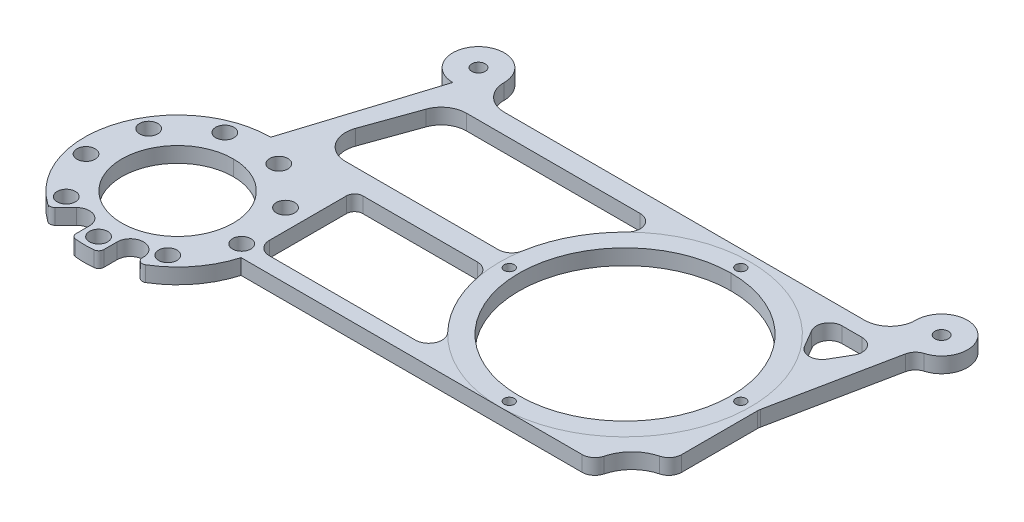
SolidWorks part; units mm, degrees
material "6061-T6 (SS)"
ref_plane "Front Plane" through (0, 0, 0) normal (0, 0, 1) x (1, 0, 0)
ref_plane "Top Plane" through (0, 0, 0) normal (0, 1, 0) x (1, 0, 0)
ref_plane "Right Plane" through (0, 0, 0) normal (1, 0, 0) x (0, 0, -1)
sketch "Sketch5" plane through (0, 0, 0) normal (0, 1, 0) x (-1, 0, 0)
  line L0 (0, 0) -> (0, 61.9125) construction
  line L1 (0, 0) -> (0, -61.9125) construction
  line L2 (0, 0) -> (-61.9125, 0) construction
  line L3 (0, 0) -> (61.9125, 0) construction
  line L4 (171.7713, 49.0982) -> (171.7713, 88.098) construction
  line L5 (-91.0543, 67.1325) -> (-91.0543, -77.9015)
  line L6 (18.2889, -77.9015) -> (18.2889, -74.5116)
  line L7 (18.2889, -77.9015) -> (150.2457, -77.9015)
  line L8 (-78.3543, -77.9015) -> (18.2889, -77.9015)
  line L9 (-78.3543, 67.1325) -> (-78.3543, -77.9015)
  line L14 (-65.6543, 67.1325) -> (0, 61.9125)
  line L15 (0, 61.9125) -> (148.0838, 88.5001)
  line L16 (150.2457, -65.2015) -> (171.7713, 3.1242)
  line L17 (0, 61.9125) -> (148.0838, 88.5001)
  line L18 (-52.9543, -65.2015) -> (124.8457, -65.2015)
  line L19 (167.2211, 94.8465) -> (167.2211, 96.424) construction
  line L22 (194.9712, 86.4149) -> (189.7063, 81.15)
  line L23 (178.6101, 85.7462) -> (178.6101, 92.3189)
  line L24 (164.9325, 92.3189) -> (164.9325, 85.7462)
  line L25 (151.9325, 85.7462) -> (151.9325, 86.3232)
  circle A0 centre (0, 57.15) radius 2.5
  circle A1 centre (57.15, 0) radius 2.5
  circle A3 centre (0, -57.15) radius 2.5
  circle A5 centre (-78.3543, 67.1325) radius 12.7
  circle A7 centre (-78.3543, -77.9015) radius 12.7
  circle A9 centre (150.2457, -77.9015) radius 12.7
  circle A11 centre (171.7713, 49.0982) radius 27.4955
  circle A13 centre (146.7027, 78.9738) radius 4.5
  circle A15 centre (171.7713, 88.098) radius 4.5
  circle A17 centre (196.8399, 78.9738) radius 4.5
  circle A18 centre (133.364, 55.8705) radius 4.5
  circle A19 centre (210.1787, 55.8704) radius 4.5
  circle A21 centre (205.5461, 29.5983) radius 4.5
  circle A22 centre (185.11, 12.4503) radius 4.5
  circle A23 centre (158.4326, 12.4503) radius 4.5
  circle A24 centre (0, 0) radius 61.9125
  circle A25 centre (0, 0) radius 52.3875
  circle A28 centre (137.9964, 29.5983) radius 4.5
  arc A29 (-52.9543, -65.2015) -> (-65.6543, -77.9015) centre (-52.9543, -77.9015) ccw
  arc A30 (137.5457, -77.9015) -> (124.8457, -65.2015) centre (124.8457, -77.9015) ccw
  circle A35 centre (-57.15, 0) radius 2.5
  arc A44 (148.0838, 88.5001) -> (198.229, 86.6961) centre (171.7713, 49.0982) ccw
  arc A45 (198.229, 86.6961) -> (194.9712, 86.4149) centre (196.7672, 84.6189) ccw
  arc A46 (178.6101, 85.7462) -> (189.7063, 81.15) centre (185.1101, 85.7462) ccw
  arc A47 (178.6101, 92.3189) -> (176.3215, 94.8465) centre (176.0701, 92.3189) ccw
  arc A48 (176.3215, 94.8465) -> (167.2211, 94.8465) centre (171.7713, 49.0982) ccw
  arc A49 (167.2211, 94.8465) -> (164.9325, 92.3189) centre (167.4725, 92.3189) ccw
  arc A50 (151.9325, 85.7462) -> (164.9325, 85.7462) centre (158.4325, 85.7462) ccw
  arc A51 (151.9325, 86.3232) -> (148.0838, 88.5001) centre (149.3925, 86.3232) ccw
  point P33 (0, 0)
  point P50 (171.7713, 95.0722)
  point P53 (151.9325, 86.0347)
  point P83 (171.7713, 49.0982)
  dimension "D1" = 123.825
  dimension "D2" = 104.775
  dimension "D4" = 5
  dimension "D8" = 45.974
  dimension "D9" = 6.5
  dimension "D10" = 6.5
  dimension "D11" = 36.648
  dimension "D12" = 2.54
  dimension "D14" = 45.974
  dimension "D15" = 13.3388
  dimension "D16" = 13.3388
  dimension "D39" = 25.4
  dimension "D40" = 9
  dimension "D41" = 38.4073
  dimension "D43" = 54.991
  dimension "D46" = 38.4073
  dimension "D50" = 25.4
  dimension "D51" = 25.4
  dimension "D3" = 57.15
  dimension "D6" = 171.7713
  dimension "D7" = 49.0982
  dimension "D13" = 7.4457
  dimension "D17" = 6.5727
  dimension "D18" = 36.648
  dimension "D19" = 22.3788
  dimension "D20" = 37.225
  dimension "D21" = 43.2207
  dimension "D22" = 4.2988
  dimension "D23" = 6.8388
  dimension "D24" = 13.6776
  dimension "D25" = 43.2207
  dimension "D26" = 4.2988
  dimension "D27" = 35.5207
  dimension "D28" = 24.9959
  dimension "D29" = 45.974
  dimension "D30" = 45.7483
  dimension "D31" = 0.577
  dimension "D32" = 36.9365
  dimension "D33" = 9.9821
  dimension "D34" = 110.49
  dimension "D35" = 77.9015
  dimension "D36" = 145.034
  dimension "D37" = 90
  dimension "D38" = 228.6
  dimension "D42" = 6.7723
  dimension "D45" = 38.9998
  dimension "D47" = 145.034
  dimension "D48" = 3.3899
  dimension "D49" = 96.6432
  dimension "D52" = 1.5775
  dimension "D5" = 4
  dimension "D44" = 9
extrude "Boss-Extrude2" add sketch "Sketch5" along normal blind 7.62
sketch "Sketch7" plane through (0, 7.62, 0) normal (0, 1, 0) x (1, 0, 0)
  line L0 (0, 0) -> (78.3543, 0) construction
  line L1 (78.3543, -54.4325) -> (78.3543, 65.2015) construction
  line L2 (78.3543, -90.6015) -> (78.3543, 90.6015)
  line L3 (78.3543, 77.9015) -> (-162.9457, 77.9015)
  arc A0 (78.3543, 65.2015) -> (65.6543, 77.9015) centre (78.3543, 77.9015) ccw construction
  circle A1 centre (78.3543, 77.9015) radius 3.302
  circle A2 centre (78.3543, -67.1325) radius 3.302
  arc A3 (-137.5457, 77.9015) -> (-150.2457, 65.2015) centre (-150.2457, 77.9015) ccw construction
  circle A4 centre (-150.2457, 77.9015) radius 3.302
  point P12 (78.3543, 0)
  dimension "D2" = 6.604
extrude "Cut-Extrude1" cut sketch "Sketch7" against normal up to next contours L2 A1 | A4 | A2
ref_plane "Plane1" through (0, 0, 0) normal (-1, 0, 0) x (0, 0, 1)
split line "Split Line1"
ref_point "Point1"
ref_plane "Plane2" through (-171.7713, 0, 0) normal (-1, 0, 0) x (0, 0, 1)
split line "Split Line2"
sketch "Sketch8" plane through (0, 7.62, 0) normal (0, 1, 0) x (1, 0, 0)
  circle A0 centre (0, 0) radius 61.9125
split line "Split Line3"
sketch "Sketch9" plane through (0, 7.62, 0) normal (0, 1, 0) x (1, 0, 0)
  line L0 (0, 0) -> (78.3543, 0) construction
  line L1 (78.3543, -54.4325) -> (78.3543, 65.2015) construction
  line L2 (78.3543, -54.4325) -> (65.4795, -1.3732)
  line L3 (65.4269, 1.3849) -> (78.3543, 65.2015)
  line L4 (78.3543, -54.4325) -> (78.3543, 65.2015)
  arc A0 (65.4795, -1.3732) -> (65.4269, 1.3849) centre (71.6505, 0.1242) cw
  point P12 (65.1463, 0)
  dimension "D2" = 6.35
  dimension "D1" = 13.208
extrude "Cut-Extrude2" cut sketch "Sketch9" against normal up to next
fillet "Fillet1" radius 6.35 2 edges at (78.3543, 3.81, -65.2015) (78.3543, 3.81, 54.4325)
sketch "Sketch18" plane through (0, 7.62, 0) normal (0, 1, 0) x (1, 0, 0)
  line L0 (0, -61.9125) -> (-127.6193, -61.9125)
  line L1 (-148.0838, -88.5001) -> (0, -61.9125)
  arc A0 (-148.0838, -88.5001) -> (-127.6193, -61.9125) centre (-171.7713, -49.0982) ccw
extrude "Cut-Extrude18" cut sketch "Sketch18" against normal up to next
sketch "Sketch23" plane through (0, 7.62, 0) normal (0, 1, 0) x (1, 0, 0)
  line L8 (44.4047, 47.7017) -> (49.3571, 39.2253)
  line L9 (60.3227, 39.2253) -> (65.2751, 47.7017)
  line L10 (59.7923, 57.255) -> (49.8875, 57.255)
  arc A8 (60.3227, 39.2253) -> (49.3571, 39.2253) centre (54.8399, 42.4286) cw
  arc A9 (65.2751, 47.7017) -> (59.7923, 57.255) centre (59.7923, 50.905) ccw
  arc A10 (49.8875, 57.255) -> (44.4047, 47.7017) centre (49.8875, 50.905) ccw
  point P1 (42.1353, 57.6919)
  point P4 (74.0237, 57.9103)
  point P5 (56.9874, 32.1374)
  point P8 (54.8399, 29.8411)
  point P11 (70.8567, 57.255)
  dimension "D1" = 31.75
  dimension "D2" = 6.35
extrude "Cut-Extrude22" cut sketch "Sketch23" against normal up to next
sketch "Sketch24" plane through (0, 7.62, 0) normal (0, 1, 0) x (1, 0, 0)
  line L0 (-128.0218, -9.4735) -> (-128.0218, -47.5328)
  line L3 (-48.0301, 55.4673) -> (-133.7574, 55.4673)
  line L4 (-145.4625, 47.2229) -> (-154.6292, 21.5976)
  line L5 (-142.924, 4.9789) -> (-67.5303, 4.9789)
  line L6 (-121.4178, -54.1368) -> (-49.3472, -54.1368)
  line L8 (-67.4476, -5.4514) -> (-123.9997, -5.4514)
  arc A2 (-142.924, 4.9789) -> (-154.6292, 21.5976) centre (-142.924, 17.4105) cw
  arc A3 (-133.7574, 55.4673) -> (-145.4625, 47.2229) centre (-133.7574, 43.0357) ccw
  arc A4 (-128.0218, -47.5328) -> (-121.4178, -54.1368) centre (-121.4178, -47.5328) ccw
  arc A7 (-128.0218, -9.4735) -> (-123.9997, -5.4514) centre (-123.9997, -9.4735) cw
  arc A8 (-43.4007, 44.1536) -> (-61.0214, 10.4665) centre (0, 0) ccw
  circle A9 centre (0, 0) radius 61.9125 construction
  arc A10 (-60.9466, -10.8934) -> (-44.5908, -42.9513) centre (0, 0) ccw
  arc A11 (-61.0214, 10.4665) -> (-67.5303, 4.9789) centre (-67.5303, 11.5829) cw
  arc A12 (-43.4007, 44.1536) -> (-48.0301, 55.4673) centre (-48.0301, 48.8633) ccw
  arc A13 (-60.9466, -10.8934) -> (-67.4476, -5.4514) centre (-67.4476, -12.0554) ccw
  arc A14 (-44.5908, -42.9513) -> (-49.3472, -54.1368) centre (-49.3472, -47.5328) cw
  point P31 (-61.672, -5.4514)
  point P34 (-30.0394, -54.1368)
  dimension "D1" = 6.604
  dimension "D2" = 6.604
  dimension "D3" = 6.604
  dimension "D4" = 6.604
  dimension "D5" = 6.604
extrude "Cut-Extrude23" cut sketch "Sketch24" against normal up to next
sketch "Sketch25" plane through (0, 7.62, 0) normal (0, 1, 0) x (1, 0, 0)
  line L0 (65.3016, 0.003) -> (65.3016, -55.5625)
  line L1 (0, -61.9125) -> (58.9516, -61.9125)
  line L2 (65.6543, -67.1325) -> (0, -61.9125) construction
  line L3 (65.3016, 0.003) -> (77.3501, -50.2939)
  line L4 (65.6543, -67.1325) -> (0, -61.9125)
  line L5 (46.2516, -61.9125) -> (65.3016, -61.9125)
  arc A0 (65.4269, 1.3849) -> (65.4795, -1.3732) centre (71.6505, 0.1242) ccw construction
  arc A2 (65.6543, -67.1325) -> (81.7988, -54.9086) centre (78.3543, -67.1325) ccw
  arc A3 (77.3501, -50.2939) -> (81.7988, -54.9086) centre (83.521, -48.7966) ccw construction
  arc A4 (77.3501, -50.2939) -> (81.7988, -54.9086) centre (83.521, -48.7966) ccw
  arc A5 (65.3016, -42.8625) -> (46.2516, -61.9125) centre (65.3016, -61.9125) ccw
  arc A6 (65.3016, -55.5625) -> (58.9516, -61.9125) centre (58.9516, -55.5625) cw
  dimension "D1" = 38.1
  dimension "D2" = 6.35
extrude "Cut-Extrude24" cut sketch "Sketch25" against normal up to next
fillet "Fillet2" radius 6.35 2 edges at (65.3016, 3.81, 42.8625) (46.2516, 3.81, 61.9125)
